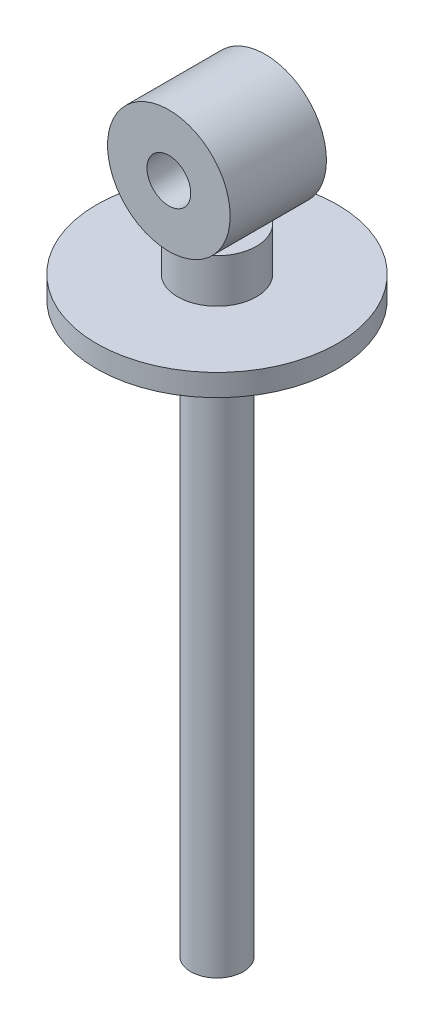
SolidWorks part; units mm, degrees
ref_plane "Спереди" through (0, 0, 0) normal (0, 0, 1) x (1, 0, 0)
ref_plane "Сверху" through (0, 0, 0) normal (0, 1, 0) x (1, 0, 0)
ref_plane "Справа" through (0, 0, 0) normal (1, 0, 0) x (0, 0, -1)
sketch "Эскиз1" plane through (0, 0, 0) normal (0, 1, 0) x (1, 0, 0)
  circle A0 centre (0, 0) radius 27.5
  point P4 (0, 0)
  point P5 (0, 0)
  dimension "D1" = 55
extrude "Бобышка-Вытянуть1" add sketch "Эскиз1" along normal blind 5
sketch "Эскиз2" plane through (0, 5, 0) normal (0, 1, 0) x (1, 0, 0)
  circle A0 centre (0, 0) radius 9
  dimension "D1" = 18
extrude "Бобышка-Вытянуть2" add sketch "Эскиз2" along normal blind 10
sketch "Эскиз3" plane through (0, 0, 0) normal (0, 0, 1) x (1, 0, 0)
  circle A0 centre (0, 29) radius 14
  circle A1 centre (0, 29) radius 5
  dimension "D1" = 28
  dimension "D3" = 10
  dimension "D2" = 14
extrude "Бобышка-Вытянуть3" add sketch "Эскиз3" along normal mid plane 22 separate body
sketch "Эскиз4" plane through (0, 0, 0) normal (0, -1, 0) x (1, 0, 0)
  circle A0 centre (0, 0) radius 6
  dimension "D1" = 12
extrude "Бобышка-Вытянуть4" add sketch "Эскиз4" along normal blind 130
